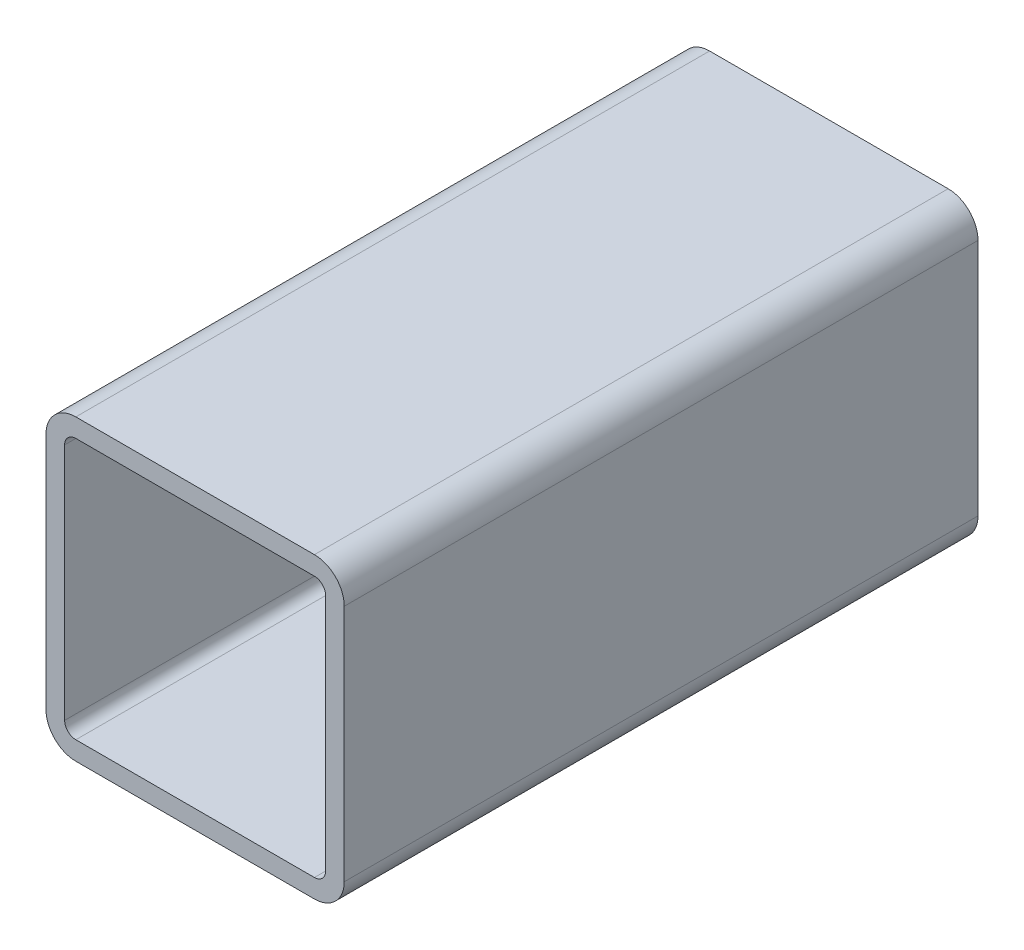
SolidWorks part; units mm, degrees
material "1.0037 (S235JR)"
ref_plane "Płaszczyzna przednia" through (0, 0, 0) normal (0, 0, 1) x (1, 0, 0)
ref_plane "Płaszczyzna górna" through (0, 0, 0) normal (0, 1, 0) x (1, 0, 0)
ref_plane "Płaszczyzna prawa" through (0, 0, 0) normal (1, 0, 0) x (0, 0, -1)
sketch "Szkic1" plane through (0, 0, 0) normal (0, 0, 1) x (1, 0, 0)
  line L1 (-560, 72) -> (-560, 8) construction
  line L2 (-488, 0) -> (-552, 0)
  line L3 (-480, 8) -> (-480, 72)
  line L4 (-488, 80) -> (-552, 80)
  line L5 (-560, 8) -> (-560, 72)
  line L6 (-560, 80) -> (0, 80) construction
  line L7 (-560, 0) -> (0, 0) construction
  line L8 (-488, 5) -> (-552, 5)
  line L9 (-555, 8) -> (-555, 72)
  line L10 (-488, 75) -> (-552, 75)
  line L11 (-485, 8) -> (-485, 72)
  arc A0 (-560, 8) -> (-552, 0) centre (-552, 8) ccw
  arc A1 (-560, 72) -> (-552, 80) centre (-552, 72) cw
  arc A2 (-488, 80) -> (-480, 72) centre (-488, 72) cw
  arc A3 (-480, 8) -> (-488, 0) centre (-488, 8) cw
  arc A4 (-555, 8) -> (-552, 5) centre (-552, 8) ccw
  arc A5 (-555, 72) -> (-552, 75) centre (-552, 72) cw
  arc A6 (-488, 75) -> (-485, 72) centre (-488, 72) cw
  arc A7 (-485, 8) -> (-488, 5) centre (-488, 8) cw
  dimension "D1" = 8
  dimension "D2" = 8
  dimension "D3" = 5
extrude "Dodanie-wyciągnięcie1" add sketch "Szkic1" along normal up to surface (170 mm away)
